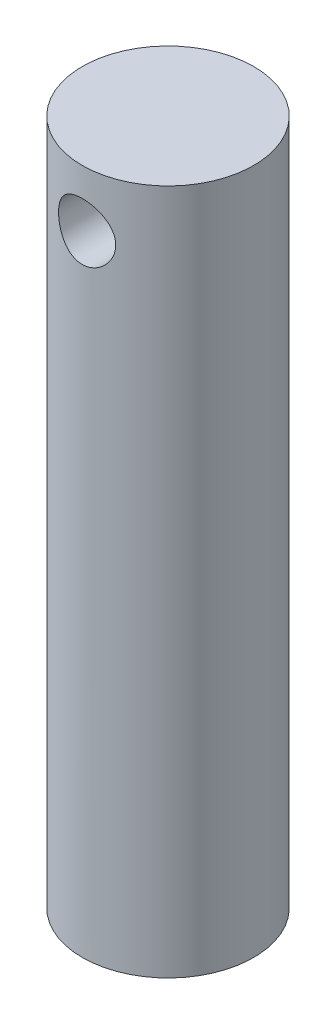
SolidWorks part; units mm, degrees
ref_plane "前视基准面" through (0, 0, 0) normal (0, 0, 1) x (1, 0, 0)
ref_plane "上视基准面" through (0, 0, 0) normal (0, 1, 0) x (1, 0, 0)
ref_plane "右视基准面" through (0, 0, 0) normal (1, 0, 0) x (0, 0, -1)
sketch "草图1" plane through (0, 0, 0) normal (0, 1, 0) x (1, 0, 0)
  circle A0 centre (0, 0) radius 75
  dimension "D1" = 150
extrude "凸台-拉伸1" add sketch "草图1" along normal blind 600
sketch "草图3" plane through (0, 0, 0) normal (0, 0, 1) x (1, 0, 0)
  line L0 (-183.4177, 600) -> (-67.664, 600) construction
  line L3 (75, 600) -> (-75, 600) construction
  line L4 (0, 600) -> (0, 550) construction
  circle A0 centre (0, 550) radius 25
  dimension "D2" = 50
  dimension "D1" = 50
extrude "切除-拉伸1" cut sketch "草图3" against normal through all both and the other way through all
